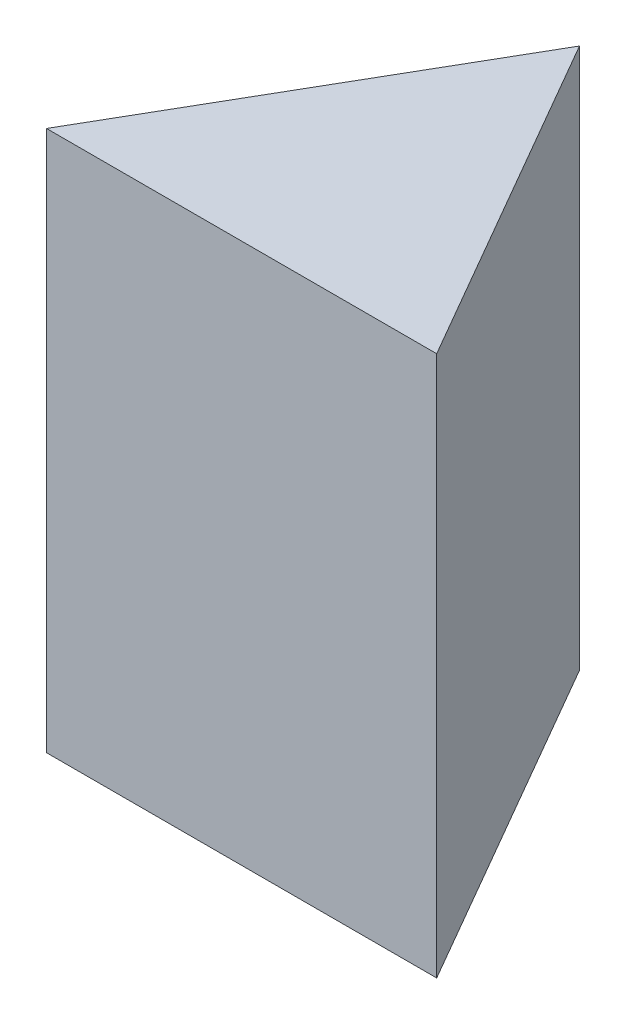
SolidWorks part; units mm, degrees
ref_plane "前视基准面" through (0, 0, 0) normal (0, 0, 1) x (1, 0, 0)
ref_plane "上视基准面" through (0, 0, 0) normal (0, 1, 0) x (1, 0, 0)
ref_plane "右视基准面" through (0, 0, 0) normal (1, 0, 0) x (0, 0, -1)
other "Configuration Table"
sketch "草图1" plane through (0, 0, 0) normal (0, 1, 0) x (1, 0, 0)
  line L0 (-21.6506, 0) -> (21.6506, 0)
  line L1 (21.6506, 0) -> (0, 37.5)
  line L2 (0, 37.5) -> (0, 0)
  line L3 (-21.6506, 0) -> (0, 37.5)
  circle A0 centre (0, 12.5) radius 25
  point P7 (0, 0)
  point P8 (0, 0)
  dimension "D1" = 50
extrude "凸台-拉伸1" add sketch "草图1" along normal blind 60 contours L3 L0 L2 | L1 L2 L0
